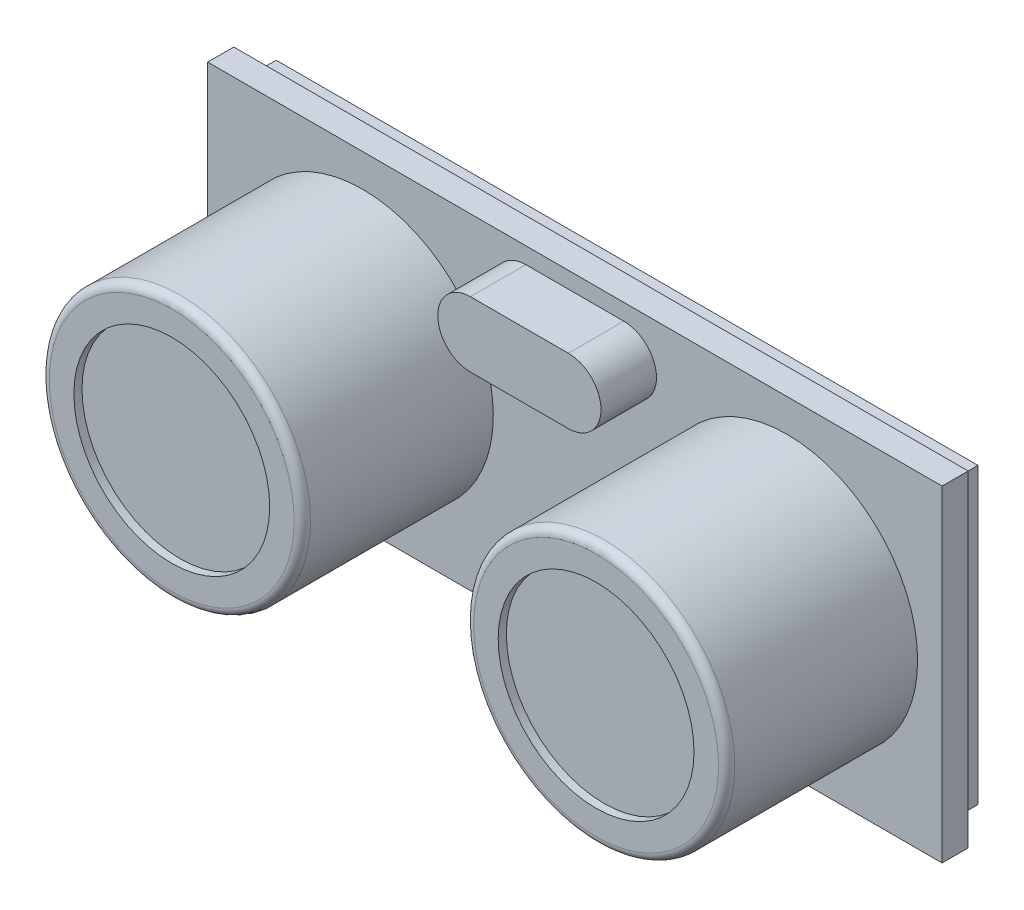
SolidWorks part; units mm, degrees
ref_plane "Спереди (XY) " through (0, 0, 0) normal (0, 0, 1) x (1, 0, 0)
ref_plane "Сверху (XZ)" through (0, 0, 0) normal (0, 1, 0) x (1, 0, 0)
ref_plane "Справа (ZY)" through (0, 0, 0) normal (1, 0, 0) x (0, 0, -1)
sketch "Эскиз1" plane through (0, 0, 0) normal (0, 0, 1) x (1, 0, 0)
  line L1 (22.5, 10) -> (-22.5, 10)
  line L2 (22.5, 10) -> (22.5, -10)
  line L3 (22.5, -10) -> (-22.5, -10)
  line L4 (-22.5, 10) -> (-22.5, -10)
  line L5 (22.5, 10) -> (-22.5, -10) construction
  line L6 (22.5, -10) -> (-22.5, 10) construction
  point P0 (0, 0)
  dimension "D1" = 20
  dimension "D2" = 45
extrude "Бобышка-Вытянуть1" add sketch "Эскиз1" along normal blind 1.6
sketch "Эскиз2" plane through (0, 0, 1.6) normal (0, 0, 1) x (1, 0, 0)
  line L0 (0, 0) -> (0, -50000) construction
  line L1 (0, 0) -> (50000, 0) construction
  circle A0 centre (-13, 0) radius 8
  circle A1 centre (13, 0) radius 8
  point P7 (-5, 0)
  dimension "D1" = 16
  dimension "D2" = 10
extrude "Бобышка-Вытянуть2" add sketch "Эскиз2" along normal blind 11.7
fillet "Скругление1" radius 0.5 2 edges at (5, 0, 13.3) (-5, 0, 13.3)
sketch "Эскиз3" plane through (0, 0, 13.3) normal (0, 0, 1) x (1, 0, 0)
  circle A0 centre (-13, 0) radius 6
  circle A1 centre (13, 0) radius 6
  dimension "D1" = 12
extrude "Вырез-Вытянуть1" cut sketch "Эскиз3" against normal blind 0.5
sketch "Эскиз4" plane through (0, 0, 1.6) normal (0, 0, 1) x (1, 0, 0)
  line L0 (-3, 7) -> (3, 7) construction
  line L1 (-3, 9) -> (3, 9)
  line L2 (-3, 5) -> (3, 5)
  arc A0 (-3, 9) -> (-3, 5) centre (-3, 7) ccw
  arc A1 (3, 5) -> (3, 9) centre (3, 7) ccw
  point P2 (0, 7)
  dimension "D1" = 4
  dimension "D2" = 10
  dimension "D3" = 7
extrude "Бобышка-Вытянуть3" add sketch "Эскиз4" along normal offset from surface (3.4 mm away) 5 up to face at (0, 0, 0)
sketch "Эскиз5" plane through (0, 0, 0) normal (0, 0, -1) x (-1, 0, 0)
  line L0 (22.5, -10) -> (-22.5, -10) construction
  line L1 (-5, -6.5) -> (5, -6.5)
  line L2 (-5, -6.5) -> (-5, -9)
  line L3 (-5, -9) -> (5, -9)
  line L4 (5, -6.5) -> (5, -9)
  line L5 (-5, -6.5) -> (5, -9) construction
  line L6 (-5, -9) -> (5, -6.5) construction
  point P0 (0, -7.75)
  dimension "D1" = 1
  dimension "D2" = 2.5
  dimension "D3" = 10
extrude "Бобышка-Вытянуть4" add sketch "Эскиз5" along normal blind 2
sketch "Эскиз6" plane through (0, 0, -2) normal (0, 0, -1) x (-1, 0, 0)
  line L0 (3.81, -7.75) -> (-3.81, -7.75) construction
  line L1 (-5, -6.5) -> (-5, -9) construction
  line L2 (0, 0) -> (0, -50000) construction
  line L4 (-4.11, -8.05) -> (-3.51, -8.05)
  line L5 (-4.11, -8.05) -> (-4.11, -7.45)
  line L6 (-4.11, -7.45) -> (-3.51, -7.45)
  line L7 (-3.51, -8.05) -> (-3.51, -7.45)
  line L8 (-4.11, -8.05) -> (-3.51, -7.45) construction
  line L9 (-4.11, -7.45) -> (-3.51, -8.05) construction
  line L10 (-1.57, -7.45) -> (-0.97, -7.45)
  line L11 (-1.57, -7.45) -> (-1.57, -8.05)
  line L12 (-1.57, -8.05) -> (-0.97, -8.05)
  line L13 (-0.97, -7.45) -> (-0.97, -8.05)
  line L14 (-1.57, -7.45) -> (-0.97, -8.05) construction
  line L15 (-1.57, -8.05) -> (-0.97, -7.45) construction
  line L16 (0.97, -7.45) -> (1.57, -7.45)
  line L17 (0.97, -7.45) -> (0.97, -8.05)
  line L18 (0.97, -8.05) -> (1.57, -8.05)
  line L19 (1.57, -7.45) -> (1.57, -8.05)
  line L20 (0.97, -7.45) -> (1.57, -8.05) construction
  line L21 (0.97, -8.05) -> (1.57, -7.45) construction
  line L22 (3.51, -7.45) -> (4.11, -7.45)
  line L23 (3.51, -7.45) -> (3.51, -8.05)
  line L24 (3.51, -8.05) -> (4.11, -8.05)
  line L25 (4.11, -7.45) -> (4.11, -8.05)
  line L26 (3.51, -7.45) -> (4.11, -8.05) construction
  line L27 (3.51, -8.05) -> (4.11, -7.45) construction
  point P4 (-5, -7.75)
  point P9 (0, -7.75)
  point P13 (-1.27, -7.75)
  point P18 (1.27, -7.75)
  dimension "D1" = 7.62
  dimension "D2" = 0.6
  dimension "D3" = 2.54
sketch "Эскиз7" plane through (0, 0, 0) normal (1, 0, 0) x (0, 0, -1)
  line L0 (2, -7.75) -> (3.5, -7.75)
  line L1 (4.1, -8.35) -> (4.1, -16)
  line L2 (-1.6, 10) -> (0, 10) construction
  line L4 (2, -7.45) -> (4.4, -7.45) construction
  line L5 (4.4, -7.45) -> (4.4, -16) construction
  line L7 (-1.6, -10) -> (-1.6, 10) construction
  line L8 (2, -7.75) -> (4.1, -7.75) construction
  line L9 (4.1, -7.75) -> (4.1, -16) construction
  arc A0 (3.5, -7.75) -> (4.1, -8.35) centre (3.5, -8.35) cw
  dimension "D4" = 0.6
  dimension "D1" = 26
  dimension "D2" = 0.3
  dimension "D3" = 6
surface "Поверхность-По траектории1"
sketch "Эскиз8" plane through (0, 0, 0) normal (0, 0, -1) x (-1, 0, 0)
  line L0 (-6, -9) -> (-6, -5.5)
  line L1 (-21.5, 9) -> (21.5, 9)
  line L2 (-21.5, 9) -> (-21.5, -9)
  line L3 (-21.5, -9) -> (-6, -9)
  line L4 (21.5, 9) -> (21.5, -9)
  line L5 (-6, -5.5) -> (6, -5.5)
  line L6 (6, -5.5) -> (6, -9)
  line L7 (6, -9) -> (21.5, -9)
  line L8 (-22.5, -10) -> (-22.5, 10) construction
  line L9 (-22.5, 10) -> (22.5, 10) construction
  line L10 (22.5, 10) -> (22.5, -10) construction
  line L11 (22.5, -10) -> (-22.5, -10) construction
  line L12 (5, -6.5) -> (-5, -6.5) construction
  line L13 (-5, -6.5) -> (-5, -9) construction
  line L14 (5, -9) -> (5, -6.5) construction
  dimension "D1" = 1
  dimension "D2" = 1
  dimension "D3" = 1
  dimension "D4" = 1
  dimension "D5" = 1
  dimension "D6" = 1
  dimension "D7" = 1
extrude "Бобышка-Вытянуть5" add sketch "Эскиз8" along normal blind 1.6
equation "\"Mass_int\"= int ( ( \"SW-Масса\" + 0.005 ) * 100 ) / 100"
